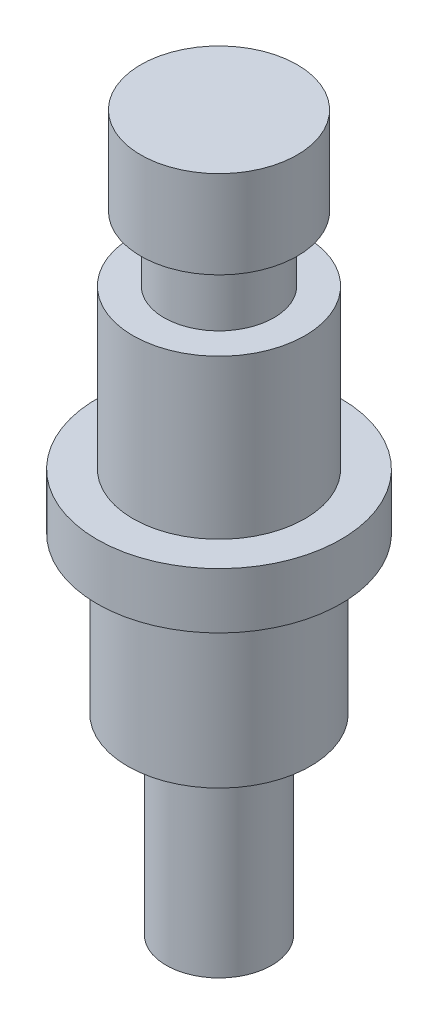
SolidWorks part; units mm, degrees
ref_plane "Front Plane" through (0, 0, 0) normal (0, 0, 1) x (1, 0, 0)
ref_plane "Top Plane" through (0, 0, 0) normal (0, 1, 0) x (1, 0, 0)
ref_plane "Right Plane" through (0, 0, 0) normal (1, 0, 0) x (0, 0, -1)
sketch "Sketch1" plane through (0, 0, 0) normal (0, 1, 0) x (1, 0, 0)
  circle A0 centre (0, 0) radius 4.77
  dimension "D1" = 9.54
extrude "Boss-Extrude1" add sketch "Sketch1" along normal blind 2.18
sketch "Sketch2" plane through (0, 0, 0) normal (0, -1, 0) x (1, 0, 0)
  circle A0 centre (0, 0) radius 3.575
  dimension "D1" = 7.15
extrude "Boss-Extrude2" add sketch "Sketch2" along normal blind 6.1
sketch "Sketch3" plane through (0, -6.1, 0) normal (0, -1, 0) x (1, 0, 0)
  circle A0 centre (0, 0) radius 2.065
  dimension "D1" = 4.13
extrude "Boss-Extrude3" add sketch "Sketch3" along normal blind 7.5
sketch "Sketch4" plane through (0, 2.18, 0) normal (0, 1, 0) x (1, 0, 0)
  circle A0 centre (0, 0) radius 3.365
  dimension "D1" = 6.73
extrude "Boss-Extrude4" add sketch "Sketch4" along normal blind 6.2
sketch "Sketch5" plane through (0, 8.38, 0) normal (0, 1, 0) x (1, 0, 0)
  circle A0 centre (0, 0) radius 2.15
  dimension "D1" = 4.3
extrude "Boss-Extrude5" add sketch "Sketch5" along normal blind 2.54
sketch "Sketch6" plane through (0, 10.92, 0) normal (0, 1, 0) x (1, 0, 0)
  circle A0 centre (0, 0) radius 3.06
  dimension "D1" = 6.12
extrude "Boss-Extrude6" add sketch "Sketch6" along normal blind 3.43
